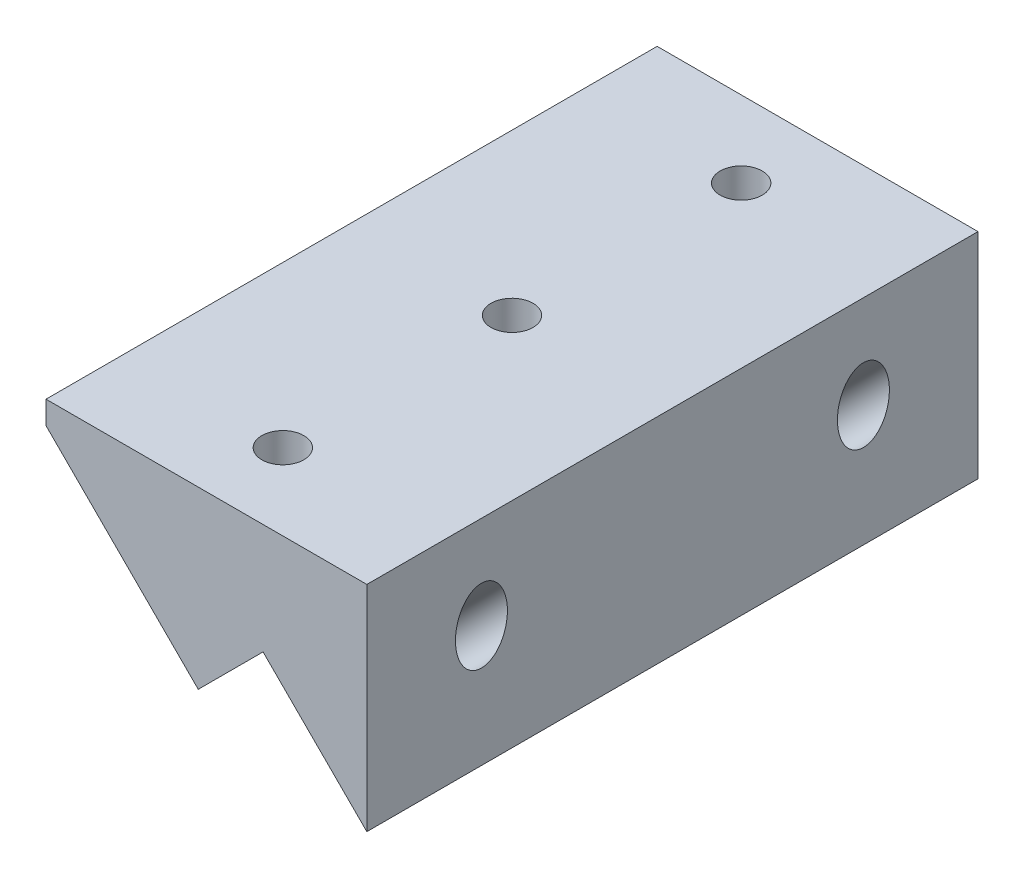
SolidWorks part; units mm, degrees
material "6061"
ref_plane "前视" through (0, 0, 0) normal (0, 0, 1) x (1, 0, 0)
ref_plane "上视" through (0, 0, 0) normal (0, 1, 0) x (1, 0, 0)
ref_plane "右视" through (0, 0, 0) normal (1, 0, 0) x (0, 0, -1)
sketch "草图1" plane through (0, 0, 0) normal (0, 0, 1) x (1, 0, 0)
  line L1 (-21, -15) -> (21, -15)
  line L2 (-21, -15) -> (-21, 15)
  line L3 (-21, 15) -> (21, 15)
  line L4 (21, -15) -> (21, 15)
  line L5 (-21, -15) -> (21, 15) construction
  line L6 (-21, 15) -> (21, -15) construction
  point P0 (0, 0)
  dimension "D1" = 42
  dimension "D2" = 30
extrude "凸台-拉伸1" add sketch "草图1" along normal mid plane 80
sketch "草图2" plane through (0, 0, 40) normal (0, 0, 1) x (1, 0, 0)
  line L0 (-21, 12) -> (6, -15)
  line L1 (-21, 15) -> (-21, -15) construction
  line L2 (-21, -15) -> (21, -15) construction
  line L3 (6, -15) -> (-21, -15)
  line L4 (-21, -15) -> (-21, 12)
  line L5 (21, 15) -> (-21, 15) construction
  dimension "D1" = 45
  dimension "D2" = 3
extrude "切除-拉伸1" cut sketch "草图2" against normal through all
hole_wizard "打孔尺寸根据内六角圆柱头螺钉的类型1" positions "草图5" profile "草图4" counterbore size "M5" standard "Gb" end condition through all
sketch "草图5" plane through (0, -15, 0) normal (0, -1, 0) x (-1, 0, 0)
  line L0 (-21, 0) -> (0, 0) construction
  line L1 (-21, -40) -> (-21, 40) construction
  line L2 (0, 0) -> (0, -40) construction
  line L4 (-21, -40) -> (21, -40) construction
  point P0 (0, -30)
  point P18 (0, 30)
  point P20 (0, 0)
  dimension "D1" = 60
sketch "草图4" plane through (0, -15, 30) normal (1, 0, 0) x (0, 0, -1)
  line L0 (0, 0) -> (0, 30)
  line L1 (0, 30) -> (2.75, 30)
  line L3 (2.75, 30) -> (2.75, 23)
  line L4 (2.75, 23) -> (5, 23)
  line L5 (5, 23) -> (5, 0)
  line L7 (5, 0) -> (0, 0)
  line L11 (0, -6.35) -> (0, 107.95) construction
  dimension "通孔孔直径" = 5.5
  dimension "通孔孔深度" = 30
  dimension "柱形沉头孔直径" = 10
  dimension "柱形沉头孔深度" = 23
sketch "草图3" plane through (0, 0, 40) normal (0, 0, 1) x (1, 0, 0)
  line L0 (-1.0711, -7.9289) -> (7.4142, 0.5563)
  line L1 (6, -15) -> (-21, 12) construction
  line L2 (7.4142, 0.5563) -> (22.9706, -15)
  line L3 (6, -15) -> (21, -15) construction
  line L4 (22.9706, -15) -> (6, -15)
  line L5 (6, -15) -> (-1.0711, -7.9289)
  dimension "D1" = 10
  dimension "D2" = 12
extrude "切除-拉伸2" cut sketch "草图3" against normal through all
hole_wizard "M8 螺纹孔1" positions "草图7" profile "草图6" tap size "M8" standard "Gb"
sketch "草图7" plane through (3.9853, 3.9853, 0) normal (-0.7071, -0.7071, 0) x (-0.7071, 0.7071, 0)
  line L0 (-24.0208, 0) -> (6.7381, 0) construction
  line L2 (-4.8492, 40) -> (-4.8492, -40) construction
  point P0 (-12.8492, 25)
  point P10 (-12.8492, -25)
  dimension "D1" = 50
  dimension "D2" = 8
sketch "草图6" plane through (13.0711, -5.1005, -25) normal (0, 0, 1) x (0.7071, -0.7071, 0)
  line L0 (0, 0) -> (0, 21.7929)
  line L1 (0, 21.7929) -> (3.4, 19.75)
  line L2 (3.4, 19.75) -> (3.4, 0)
  line L5 (3.4, 0) -> (0, 0)
  line L10 (0, 21.7929) -> (-3.4, 19.75) construction
  line L11 (0, -6.35) -> (0, 107.95) construction
  dimension "螺纹孔钻头直径" = 6.8
  dimension "螺纹孔钻头深度" = 19.75
  dimension "导头角度" = 118
cosmetic thread "孔螺蚊线1"
cosmetic thread "孔螺蚊线2"
